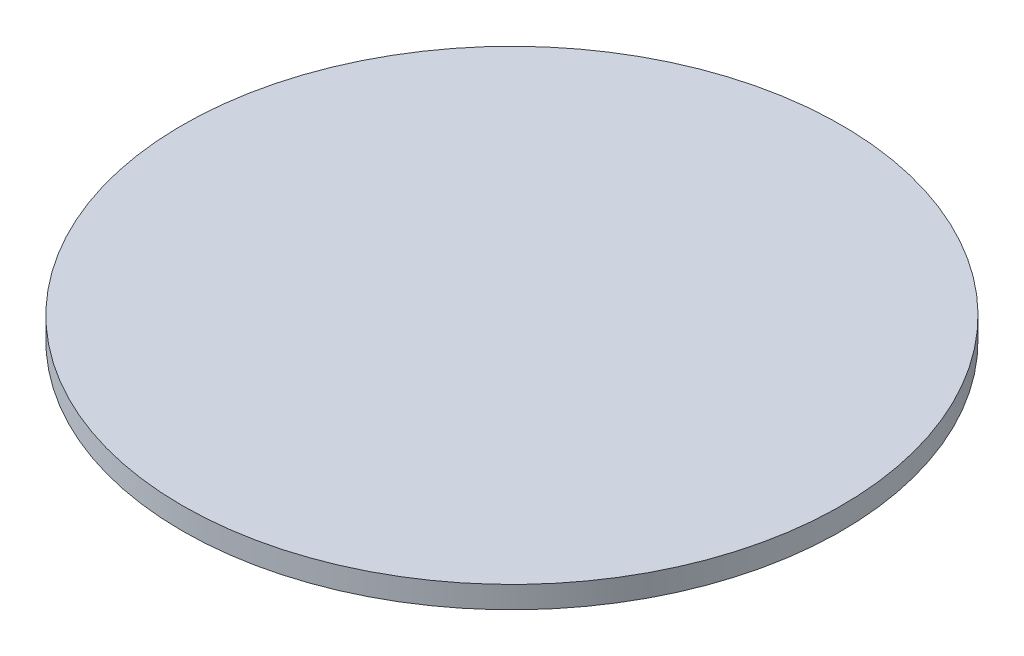
SolidWorks part; units mm, degrees
ref_plane "Front Plane" through (0, 0, 0) normal (0, 0, 1) x (1, 0, 0)
ref_plane "Top Plane" through (0, 0, 0) normal (0, 1, 0) x (1, 0, 0)
ref_plane "Right Plane" through (0, 0, 0) normal (1, 0, 0) x (0, 0, -1)
sketch "Sketch1" plane through (0, 0, 0) normal (0, 1, 0) x (1, 0, 0)
  circle A0 centre (0, 0) radius 30
  dimension "D1" = 60
extrude "Boss-Extrude1" add sketch "Sketch1" along normal blind 2
sketch "Sketch2" plane through (0, 0, 0) normal (0, -1, 0) x (1, 0, 0)
  circle A0 centre (0, 0) radius 3.5
  circle A1 centre (0, 0) radius 2.5
  dimension "D1" = 5
  dimension "D2" = 7
extrude "Boss-Extrude2" add sketch "Sketch2" along normal blind 10
fillet "Fillet1" radius 1 1 edges at (0, 0, 3.5)
fillet "Fillet2" radius 1 1 edges at (0, 0, -2.5)
